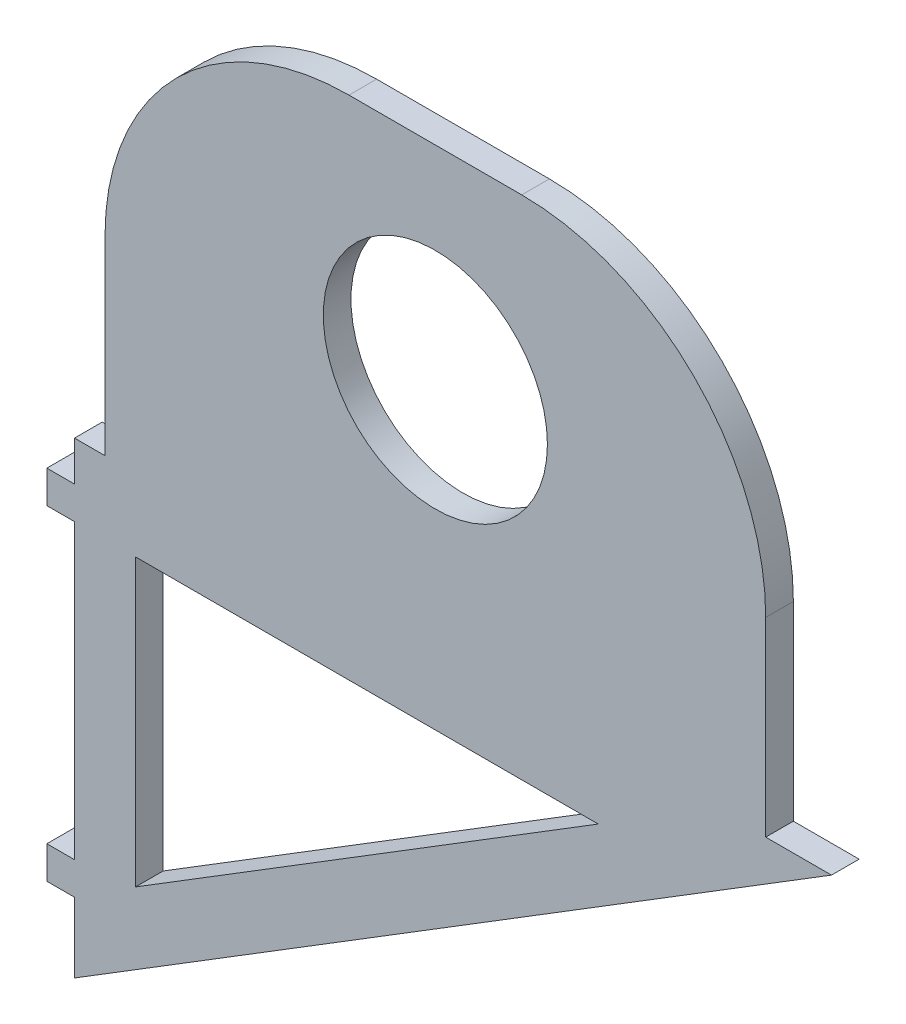
SolidWorks part; units mm, degrees
material "Delrin 2700 NC010, Low Viscosity Acetal Copolymer (SS)"
ref_plane "Front Plane" through (0, 0, 0) normal (0, 0, 1) x (1, 0, 0)
ref_plane "Top Plane" through (0, 0, 0) normal (0, 1, 0) x (1, 0, 0)
ref_plane "Right Plane" through (0, 0, 0) normal (1, 0, 0) x (0, 0, -1)
sketch "Sketch1" plane through (0, 0, 0) normal (0, 0, 1) x (1, 0, 0)
  line L0 (0, 0) -> (47.2887, 29.21)
  line L1 (3.81, 6.4008) -> (3.81, 24.6888) construction
  line L2 (3.81, 24.6888) -> (32.7193, 24.6888)
  line L4 (0, 0) -> (0, 4.3688)
  line L5 (3.81, 6.8317) -> (3.81, 24.6888)
  line L6 (3.81, 6.8317) -> (32.7193, 24.6888)
  line L44 (22.5425, 14.605) -> (22.5425, 24.13) construction
  line L46 (1.905, 29.21) -> (1.905, 56.3372)
  line L47 (1.905, 56.3372) -> (43.18, 56.3372)
  line L48 (43.18, 29.21) -> (43.18, 56.3372)
  line L49 (1.905, 43.6372) -> (43.18, 43.6372) construction
  line L55 (1.905, 29.21) -> (0, 29.21)
  line L56 (0, 26.7208) -> (-1.7272, 26.7208)
  line L57 (-1.7272, 6.4008) -> (-1.7272, 4.3688)
  line L58 (0, 24.6888) -> (-1.7272, 24.6888)
  line L59 (-1.7272, 26.7208) -> (-1.7272, 24.6888)
  line L70 (0, 26.7208) -> (0, 29.21)
  line L74 (0, 4.3688) -> (-1.7272, 4.3688)
  line L75 (0, 6.4008) -> (-1.7272, 6.4008)
  line L76 (0, 6.4008) -> (0, 24.6888)
  line L108 (47.2887, 29.21) -> (43.18, 29.21)
  circle A0 centre (22.5425, 43.6372) radius 7
  point P56 (22.5425, 43.6372)
  point P60 (22.5425, 56.3372)
  dimension "D14" = 12.7
  dimension "D3" = 14
  dimension "D2" = 29.21
  dimension "D12" = 41.275
  dimension "D16" = 2.032
  dimension "D17" = 1.7272
  dimension "D25" = 1.905
  dimension "D5" = 3.81
  dimension "D24" = 2
extrude "Boss-Extrude1" add sketch "Sketch1" along normal blind 1.7272
fillet "Fillet7" radius 15.24 2 edges at (1.905, 56.3372, 0.8636) (43.18, 56.3372, 0.8636)
sketch "Sketch2" plane through (0, 0, 0) normal (1, 0, 0) x (0, 0, -1)
  line L0 (0, 26.7208) -> (0, 24.6888) construction
  line L1 (0, 24.6888) -> (-1.7272, 24.6888) construction
  line L2 (-1.7272, 24.6888) -> (-1.7272, 26.7208) construction
  line L3 (-1.7272, 26.7208) -> (0, 26.7208) construction
  line L4 (0, 6.4008) -> (0, 4.3688) construction
  line L5 (0, 4.3688) -> (-1.7272, 4.3688) construction
  line L6 (-1.7272, 4.3688) -> (-1.7272, 6.4008) construction
  line L7 (-1.7272, 6.4008) -> (0, 6.4008) construction
  line L8 (0, 26.7208) -> (0, 24.6888)
  line L9 (0, 24.6888) -> (-1.7272, 24.6888)
  line L10 (-1.7272, 24.6888) -> (-1.7272, 26.7208)
  line L11 (-1.7272, 26.7208) -> (0, 26.7208)
  line L12 (0, 6.4008) -> (0, 4.3688)
  line L13 (0, 4.3688) -> (-1.7272, 4.3688)
  line L14 (-1.7272, 4.3688) -> (-1.7272, 6.4008)
  line L15 (-1.7272, 6.4008) -> (0, 6.4008)
